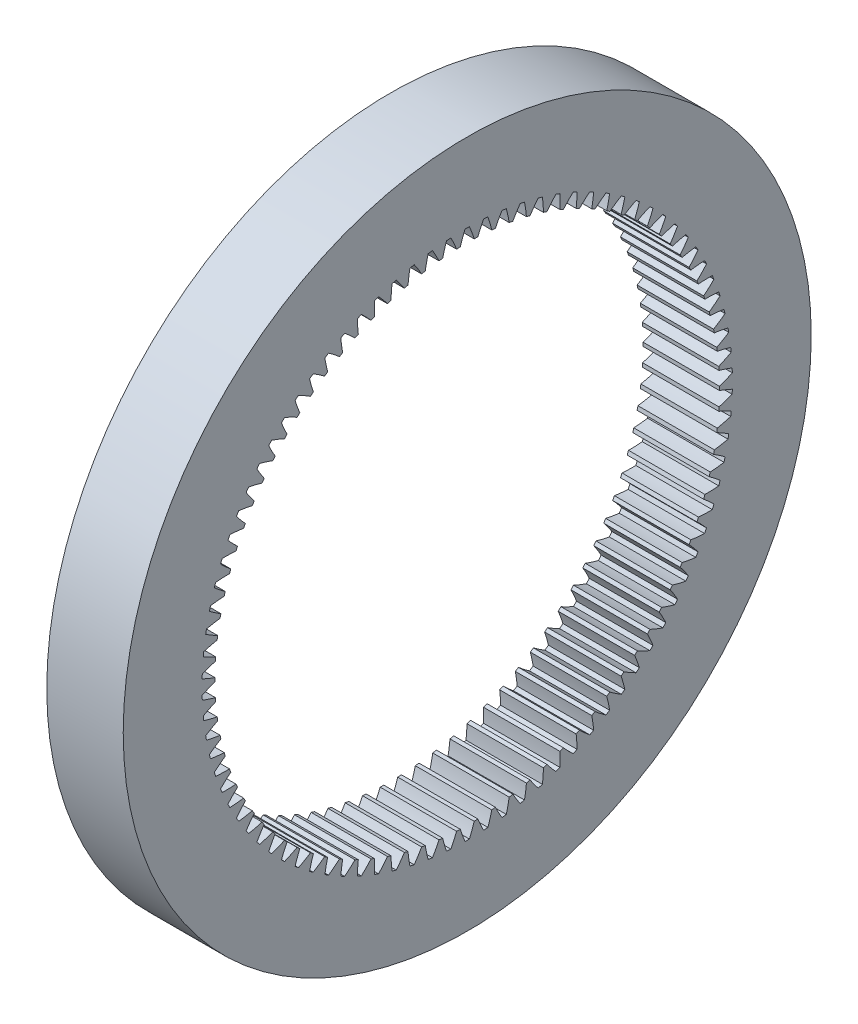
SolidWorks part; units mm, degrees
ref_plane "Plane1" through (0, 0, 0) normal (0, 0, 1) x (1, 0, 0)
ref_plane "Plane2" through (0, 0, 0) normal (0, 1, 0) x (1, 0, 0)
ref_plane "Plane3" through (0, 0, 0) normal (1, 0, 0) x (0, 0, -1)
other "Configuration Table"
sketch "HoldingSke" plane through (0, 0, 0) normal (0, 1, 0) x (1, 0, 0)
  line L0 (0, 0) -> (0, -0.6667)
  line L1 (-15, 0) -> (100, 0) construction
  line L2 (0, 0) -> (-2.1039, 2.3779)
  line L3 (0, 0) -> (-11.863, 4.5341)
  line L4 (0, 0) -> (0, 8.636)
  line L5 (0, 0) -> (-23.7986, -8.8762)
  line L6 (0, 0) -> (-10.5278, -7.1032)
  line L7 (-2.1039, 2.3779) -> (3.3635, 27.1825)
  line L8 (-76.2, 3.8779) -> (-54.61, 3.8779)
  line L9 (-71.009, 38.7566) -> (-53.1078, 45.2721)
  line L10 (-76.2, 71.12) -> (104.1128, 71.12)
  line L11 (0, 0) -> (-20, 0)
  line L12 (-76.2, 101.6) -> (-76.147, 101.6)
  line L13 (24.9733, 27.94) -> (52.9518, 28.4284)
  line L14 (24.9733, 27.94) -> (24.9743, 27.94)
  line L15 (24.9733, 27.94) -> (100.4006, 29.5858)
  circle A0 centre (0, 0) radius 90
  circle A1 centre (0, 0) radius 12.7
  circle A2 centre (0, 0) radius 12.7
  dimension "MHD" = 25.4
  dimension "Hub_dia" = 25.4
  dimension "Diameter" = 180
  dimension "Num_teeth" = 90
  dimension "Pitch" = 0.6667
  dimension "Overall_len" = 25.4
  dimension "Show_teeth" = 90
  dimension "Thickness" = 12.7
  dimension "OAL" = 25.4001
  dimension "T_dim" = 21.59
  dimension "Ap" = 20
  dimension "H" = 19.05
  dimension "Pitch_radius" = 180.3128
  dimension "Width" = 20
  dimension "Backlash" = 0.053
  dimension "Addendum_fac" = 1
  dimension "Dedendum_fac" = 1.25
  dimension "Clearance_fac" = 0.25
  dimension "Dedendum_add" = 0.001
  dimension "Module" = 1.5
sketch "BasProSke" plane through (0, 0, 0) normal (0, 1, 0) x (1, 0, 0)
  line L0 (-10, 0) -> (60, 0) construction
  line L1 (0, 66) -> (0, 90)
  line L2 (0, 66) -> (20, 66)
  line L3 (20, 66) -> (20, 90)
  line L4 (20, 90) -> (0, 90)
  dimension "Diameter" = 180
  dimension "Thickness" = 20
  dimension "Inside_diameter" = 132
revolve "Base-Revolve" add sketch "BasProSke" angle 360 about L0
sketch "TooCutSke" plane through (0, 0, 0) normal (1, 0, 0) x (0, 0, -1)
  line L3 (1.3105, 67.4873) -> (1.3105, 53.6633) construction
  line L4 (0, 0) -> (0, 59.563) construction
  line L5 (0, 0) -> (-2.3846, 68.2859) construction
  line L6 (-30.4453, 56.058) -> (35.8275, 58.3722) construction
  circle A0 centre (0, 0) radius 67.5 construction
  circle A1 centre (0, 0) radius 69.376 construction
  circle A2 centre (0, 0) radius 57.0863 construction
  circle A3 centre (0, 0) radius 65.9746 construction
  arc A4 (1.8227, 65.9494) -> (0.5669, 69.3737) centre (-30.4453, 56.058) ccw
  arc A5 (1.8227, 65.9494) -> (-1.8227, 65.9494) centre (0, 0) ccw
  arc A6 (0.5669, 69.3737) -> (-0.5669, 69.3737) centre (0, 0) ccw
  arc A7 (-0.5669, 69.3737) -> (-1.8227, 65.9494) centre (30.4453, 56.058) ccw
  dimension "Pitch_dia" = 135
  dimension "Base_dia" = 114.1727
  dimension "Root_dia" = 138.752
  dimension "Overcut_dia" = 131.9492
  dimension "Flank_rad" = 33.75
  dimension "Half_ang" = 2
  dimension "Half_CT" = 1.3105
extrude "ToothCut" cut sketch "TooCutSke" along normal through all
fillet "Breaks" [suppressed] radius 0.15
fillet "RootFillets" [suppressed] radius 0.376
pattern_circular "TeethCuts" count 90 every 4 about axis through (-10, 0, 0) along (1, 0, 0) of "RootFillets", "Breaks", "ToothCut"
equation "' \"Module@HoldingSke\" = 6.35"
equation "' \"Num_teeth@HoldingSke\" = 24"
equation "' \"Ap@HoldingSke\" =  14.5"
equation "' \"Ap@HoldingSke\" = 14.5"
equation "' \"Width@HoldingSke\" = 12"
equation "' \"Diameter@HoldingSke\" = 8 * 25.4"
equation "' \"Show_teeth@HoldingSke\" = 100"
equation "' \"Backlash@HoldingSke\" = 0.009 * 25.4"
equation "' \"Addendum_fac@HoldingSke\" = 1.0"
equation "' \"Dedendum_fac@HoldingSke\" = 1.25"
equation "' \"Dedendum_add@HoldingSke\" = 0.00005 * 25.4"
equation "' \"Clearance_fac@HoldingSke\" = 0.25"
equation "\"Pitch@HoldingSke\" = 1 / \"Module@HoldingSke\" "
equation "\"Overcut_dia@TooCutSke\" = (\"Num_teeth@HoldingSke\" - 2 * \"Addendum_fac@HoldingSke\") / \"Pitch@HoldingSke\" - 0.002 * 25.4"
equation "\"Pitch_dia@TooCutSke\" = \"Num_teeth@HoldingSke\" / \"Pitch@HoldingSke\""
equation "\"Base_dia@TooCutSke\" = \"Num_teeth@HoldingSke\" / \"Pitch@HoldingSke\" * cos((\"Ap@HoldingSke\"  * 3.14159265 / 180)) * 0.90"
equation "\"Root_dia@TooCutSke\" = \"Num_teeth@HoldingSke\"  / \"Pitch@HoldingSke\" + 2 *  \"Dedendum_fac@HoldingSke\"/ \"Pitch@HoldingSke\" + \"Dedendum_add@HoldingSke\" * 2"
equation "\"Half_ang@TooCutSke\" = 180 / \"Num_teeth@HoldingSke\""
equation "\"Half_CT@TooCutSke\" = \"Num_teeth@HoldingSke\" / \"Pitch@HoldingSke\" * sin((3.14159265 / 2 / \"Num_teeth@HoldingSke\")) / 2 + 10 * \"Backlash@HoldingSke\" / 4"
equation "\"Flank_rad@TooCutSke\" = \"Num_teeth@HoldingSke\" / \"Pitch@HoldingSke\" / 4"
equation "\"Radius@RootFillets\"= \"Clearance_fac@HoldingSke\" / \"Pitch@HoldingSke\" + \"Dedendum_add@HoldingSke\""
equation "\"Break_rad@Breaks\" = 0.02 / \"Pitch@HoldingSke\" * 5"
equation "\"Num_teeth@TeethCuts\" = int( \"Show_teeth@HoldingSke\" ) + 1"
equation "\"Num_teeth@TeethCuts\" = ((sgn( \"Num_teeth@TeethCuts\" - \"Num_teeth@HoldingSke\" )-1)*( \"Num_teeth@TeethCuts\" - \"Num_teeth@HoldingSke\" ))/-2+ \"Num_teeth@HoldingSke\""
equation "\"Num_teeth@TeethCuts\" = ((sgn( \"Num_teeth@TeethCuts\" - 2.0)+1)*( \"Num_teeth@TeethCuts\" - 2.0))/2 +2.0"
equation "\"Angle@TeethCuts\" = 360.0 / \"Num_teeth@HoldingSke\""
equation "\"Diameter@BasProSke\" = \"Num_teeth@HoldingSke\"  / \"Pitch@HoldingSke\" + 2 *  \"Dedendum_fac@HoldingSke\"/ \"Pitch@HoldingSke\" + \"Dedendum_add@HoldingSke\" * 2 + 0.002 * 25.4"
equation "\"Diameter@BasProSke\" = ((sgn( \"Diameter@BasProSke\"  - \"Diameter@HoldingSke\" )+1)*( \"Diameter@BasProSke\"  - \"Diameter@HoldingSke\" ))/2 + \"Diameter@HoldingSke\""
equation "\"Inside_diameter@BasProSke\" =  (\"Num_teeth@HoldingSke\" - 2 * \"Addendum_fac@HoldingSke\") / \"Pitch@HoldingSke\" "
equation "\"Thickness@BasProSke\"  = \"Width@HoldingSke\""
